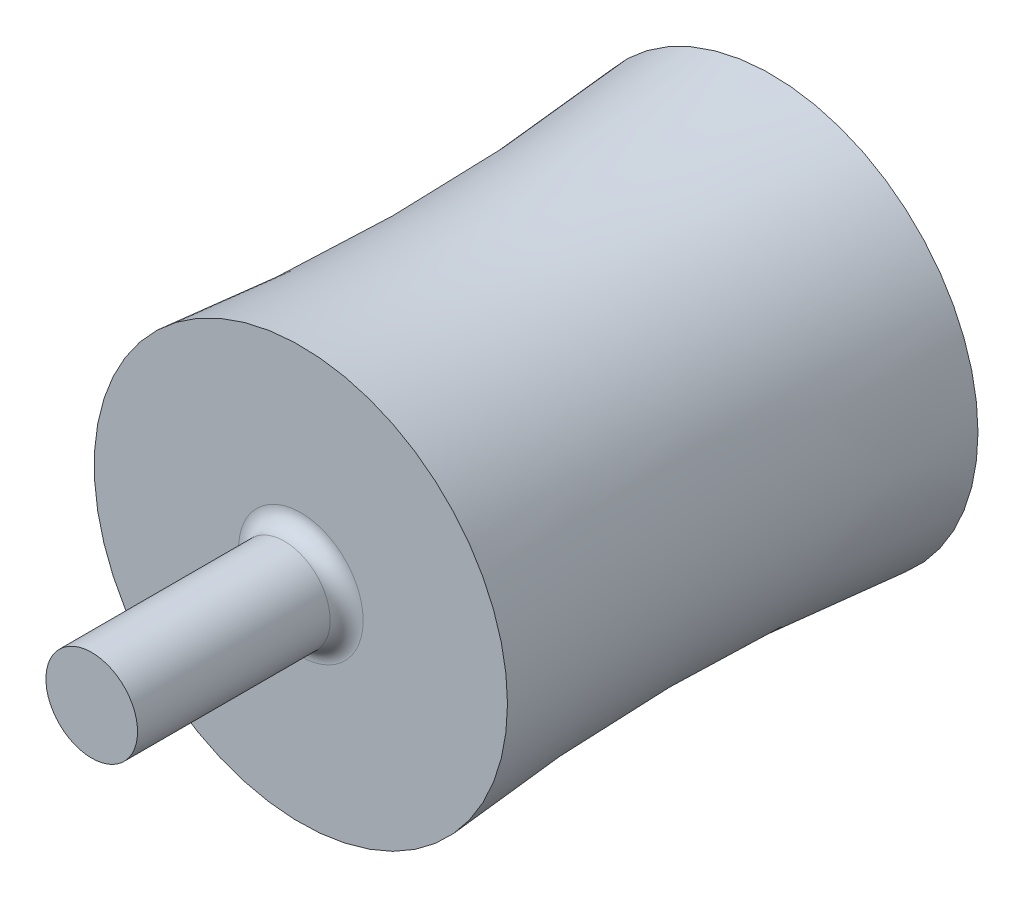
SolidWorks part; units mm, degrees
ref_plane "Plan de face" through (0, 0, 0) normal (0, 0, 1) x (1, 0, 0)
ref_plane "Plan de dessus" through (0, 0, 0) normal (0, 1, 0) x (1, 0, 0)
ref_plane "Plan de droite" through (0, 0, 0) normal (1, 0, 0) x (0, 0, -1)
sketch "Esquisse1" plane through (0, 0, 0) normal (0, 0, 1) x (1, 0, 0)
  circle A0 centre (0, 0) radius 25.1
  dimension "D1" = 50.2
extrude "Boss.-Extru.1" add sketch "Esquisse1" along normal blind 57.15
sketch "Esquisse2" plane through (0, 0, 0) normal (0, 0, -1) x (-1, 0, 0)
  circle A0 centre (0, 0) radius 21.25
  dimension "D1" = 42.5
extrude "Enlèv. mat.-Extru.1" cut sketch "Esquisse2" against normal blind 53.975
sketch "Esquisse3" plane through (0, 0, 57.15) normal (0, 0, 1) x (1, 0, 0)
  circle A0 centre (0, 0) radius 5.5652
  dimension "D1" = 11.1305
extrude "Boss.-Extru.2" add sketch "Esquisse3" along normal blind 25.4
fillet "Congé1" radius 2 1 edges at (-21.25, 0, 0)
fillet "Congé2" radius 2 1 edges at (5.5652, 0, 57.15)
sketch "Esquisse4" plane through (0, 0, 0) normal (1, 0, 0) x (0, 0, -1)
  line L0 (-82.55, 0) -> (0, 0) construction
  line L1 (-82.55, 5.5652) -> (-82.55, -5.5652) construction
  line L2 (-57.15, 25.1) -> (0, 25.1)
  arc A0 (-57.15, 25.1) -> (0, 25.1) centre (-28.575, 277.4875) ccw
  dimension "D1" = 254
revolve "Enlèvement de matière-Révolution1" cut sketch "Esquisse4" angle 360 about L0
